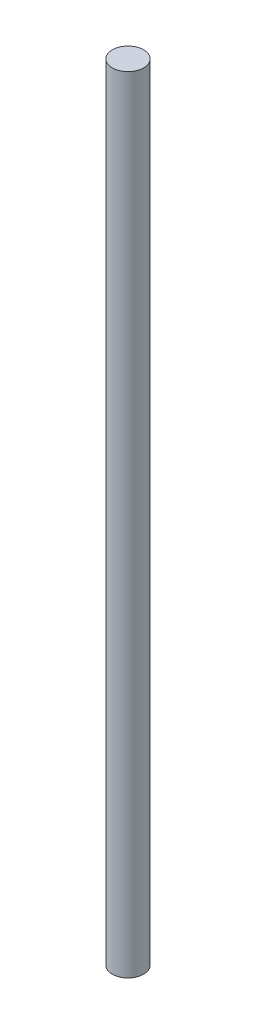
SolidWorks part; units mm, degrees
ref_plane "前视基准面" through (0, 0, 0) normal (0, 0, 1) x (1, 0, 0)
ref_plane "上视基准面" through (0, 0, 0) normal (0, 1, 0) x (1, 0, 0)
ref_plane "右视基准面" through (0, 0, 0) normal (1, 0, 0) x (0, 0, -1)
other "Configuration Table"
sketch "草图2" plane through (0, 0, 0) normal (0, 1, 0) x (1, 0, 0)
  circle A0 centre (0, 0) radius 2
  dimension "D1" = 4
extrude "凸台-拉伸2" add sketch "草图2" along normal blind 100
